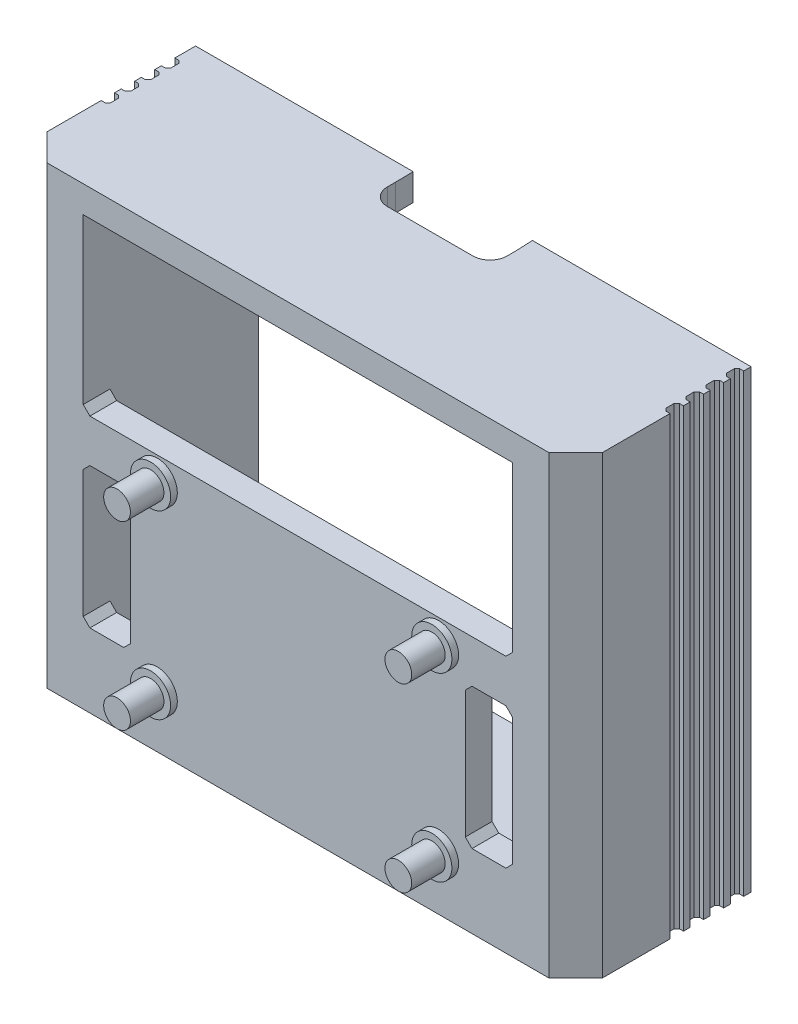
SolidWorks part; units mm, degrees
ref_plane "前视基准面" through (0, 0, 0) normal (0, 0, 1) x (1, 0, 0)
ref_plane "上视基准面" through (0, 0, 0) normal (0, 1, 0) x (1, 0, 0)
ref_plane "右视基准面" through (0, 0, 0) normal (1, 0, 0) x (0, 0, -1)
sketch "草图1" plane through (0, 0, 0) normal (0, 0, 1) x (1, 0, 0)
  line L4 (-16.0288, 20.4363) -> (-20.7373, 20.4363)
  line L5 (-20.7373, 20.4363) -> (-20.7373, -9.5383)
  line L6 (-20.7373, -9.5383) -> (-16.0288, -9.5383)
  line L7 (-16.0288, -9.5383) -> (-16.0288, 20.4363)
  line L8 (-16.0288, 20.4363) -> (-20.7373, 20.4363)
  line L9 (-20.7373, 20.4363) -> (-20.7373, -9.5383)
  line L10 (-20.7373, -9.5383) -> (-16.0288, -9.5383)
  line L11 (-16.0288, -9.5383) -> (-16.0288, 20.4363)
  line L12 (20.7373, -9.5383) -> (20.7373, 20.4363)
  line L13 (20.7373, 20.4363) -> (16.0288, 20.4363)
  line L14 (16.0288, 20.4363) -> (16.0288, -9.5383)
  line L15 (16.0288, -9.5383) -> (20.7373, -9.5383)
  line L16 (20.7373, -9.5383) -> (20.7373, 20.4363)
  line L17 (20.7373, 20.4363) -> (16.0288, 20.4363)
  line L18 (16.0288, 20.4363) -> (16.0288, -9.5383)
  line L19 (16.0288, -9.5383) -> (20.7373, -9.5383)
  dimension "D1" = 0
  dimension "D2" = 0
extrude "凸台-拉伸1" add sketch "草图1" along normal up to vertex (4.1 mm away)
sketch "草图2" plane through (0, 0, 4.1) normal (0, 0, 1) x (1, 0, 0)
  line L4 (-16.0288, -9.5383) -> (-16.0288, 20.4363)
  line L5 (-16.0288, 20.4363) -> (-20.7373, 20.4363)
  line L6 (-20.7373, 20.4363) -> (-20.7373, -9.5383)
  line L7 (-20.7373, -9.5383) -> (-16.0288, -9.5383)
  line L8 (-16.0288, -9.5383) -> (-16.0288, 20.4363)
  line L9 (-16.0288, 20.4363) -> (-20.7373, 20.4363)
  line L10 (-20.7373, 20.4363) -> (-20.7373, -9.5383)
  line L11 (-20.7373, -9.5383) -> (-16.0288, -9.5383)
  line L12 (16.0288, -9.5383) -> (20.7373, -9.5383)
  line L13 (20.7373, -9.5383) -> (20.7373, 20.4363)
  line L14 (20.7373, 20.4363) -> (16.0288, 20.4363)
  line L15 (16.0288, 20.4363) -> (16.0288, -9.5383)
  line L16 (16.0288, -9.5383) -> (20.7373, -9.5383)
  line L17 (20.7373, -9.5383) -> (20.7373, 20.4363)
  line L18 (20.7373, 20.4363) -> (16.0288, 20.4363)
  line L19 (16.0288, 20.4363) -> (16.0288, -9.5383)
  dimension "D1" = 0
  dimension "D2" = 0
extrude "凸台-拉伸2" add sketch "草图2" along normal blind 9
sketch "草图3" plane through (16.0288, 0, 0) normal (-1, 0, 0) x (0, 0, 1)
  line L0 (13.1, -9.5383) -> (7.1, -9.5383)
  line L1 (7.1, -9.5383) -> (7.1, 20.4363)
  line L4 (0, 20.4363) -> (0, -9.5383)
  line L5 (0, -9.5383) -> (13.1, -9.5383)
  line L6 (13.1, -9.5383) -> (13.1, 20.4363)
  line L7 (13.1, 20.4363) -> (0, 20.4363)
  line L9 (7.1, -9.5383) -> (13.1, -9.5383)
  line L10 (13.1, -9.5383) -> (13.1, 20.4363)
  line L11 (13.1, 20.4363) -> (7.1, 20.4363)
  line M6 (0, -9.5383) -> (13.1, -9.5383)
  line M7 (13.1, -9.5383) -> (13.1, 20.4363)
  line M8 (13.1, 20.4363) -> (0, 20.4363)
  dimension "D1" = 0
extrude "凸台-拉伸3" add sketch "草图3" along normal up to surface (32.0576 mm away) contours L1 M6 M7 M8 up to face at (-16.0288, 5.449, 6.55)
sketch "草图5" plane through (0, -9.5383, 0) normal (0, -1, 0) x (-1, 0, 0)
  line L0 (0, -13.1) -> (0, -15.0617)
  line L1 (20.7373, -13.1) -> (-20.7373, -13.1) construction
sketch "草图6" plane through (0, 0, 13.1) normal (0, 0, 1) x (1, 0, 0)
  circle A0 centre (-10.5, 5.9617) radius 1 construction
  circle A1 centre (-10.5, 5.9617) radius 1
  circle A3 centre (10.5, -7.5383) radius 1 construction
  circle A4 centre (-10.5, -7.5383) radius 1 construction
  circle A6 centre (10.5, -7.5383) radius 1
  circle A7 centre (-10.5, -7.5383) radius 1
  circle A8 centre (10.5, 5.9617) radius 1 construction
  circle A9 centre (10.5, 5.9617) radius 1
extrude "凸台-拉伸4" add sketch "草图6" along normal blind 3
sketch "草图7" plane through (0, 0, 13.1) normal (0, 0, 1) x (1, 0, 0)
  circle A0 centre (-10.5, 5.9617) radius 1.5
  circle A1 centre (-10.5, -7.5383) radius 1.5
  circle A2 centre (10.5, -7.5383) radius 1.5
  circle A3 centre (10.5, 5.9617) radius 1.5
extrude "凸台-拉伸5" add sketch "草图7" along normal blind 0.5
sketch "草图9" plane through (0, 0, 13.1) normal (0, 0, 1) x (1, 0, 0)
  line L0 (9.5, 14.4617) -> (-9.5, 14.4617) construction
  line L1 (16.0288, 14.4617) -> (-16.0288, 14.4617)
  line L4 (-16.0288, -9.5383) -> (16.0288, -9.5383)
  line L5 (-16.0288, 20.4363) -> (-16.0288, -9.5383)
  line L6 (16.0288, 20.4363) -> (-16.0288, 20.4363)
  line L7 (16.0288, -9.5383) -> (16.0288, 20.4363)
  line L9 (-16.0288, 20.4363) -> (-16.0288, 14.4617)
  line L10 (16.0288, 20.4363) -> (-16.0288, 20.4363)
  line L11 (16.0288, 14.4617) -> (16.0288, 20.4363)
  dimension "D1" = 0
extrude "切除-拉伸1" cut sketch "草图9" against normal up to next
sketch "草图11" plane through (0, -9.5383, 0) normal (0, -1, 0) x (1, 0, 0)
  line L8 (-20.7373, 0) -> (-16.0288, 0)
  line L9 (-16.0288, 0) -> (-16.0288, 7.1)
  line L10 (-16.0288, 7.1) -> (16.0288, 7.1)
  line L11 (16.0288, 7.1) -> (16.0288, 0)
  line L12 (16.0288, 0) -> (20.7373, 0)
  line L13 (20.7373, 0) -> (20.7373, 13.1)
  line L14 (20.7373, 13.1) -> (-20.7373, 13.1)
  line L15 (-20.7373, 13.1) -> (-20.7373, 0)
  line L16 (-20.7373, 0) -> (-16.0288, 0)
  line L17 (-16.0288, 0) -> (-16.0288, 7.1)
  line L18 (-16.0288, 7.1) -> (16.0288, 7.1)
  line L19 (16.0288, 7.1) -> (16.0288, 0)
  line L20 (16.0288, 0) -> (20.7373, 0)
  line L21 (20.7373, 0) -> (20.7373, 13.1)
  line L22 (20.7373, 13.1) -> (-20.7373, 13.1)
  line L23 (-20.7373, 13.1) -> (-20.7373, 0)
  dimension "D1" = 0
extrude "凸台-拉伸6" add sketch "草图11" along normal up to surface (2 mm away)
sketch "草图12" plane through (0, 20.4363, 0) normal (0, 1, 0) x (1, 0, 0)
  line L4 (16.0288, 0) -> (16.0288, -13.1)
  line L5 (16.0288, -13.1) -> (20.7373, -13.1)
  line L6 (20.7373, -13.1) -> (20.7373, 0)
  line L7 (20.7373, 0) -> (16.0288, 0)
  line L8 (16.0288, 0) -> (16.0288, -13.1)
  line L9 (16.0288, -13.1) -> (20.7373, -13.1)
  line L10 (20.7373, -13.1) -> (20.7373, 0)
  line L11 (20.7373, 0) -> (16.0288, 0)
  line L12 (-20.7373, -13.1) -> (-16.0288, -13.1)
  line L13 (-16.0288, -13.1) -> (-16.0288, 0)
  line L14 (-16.0288, 0) -> (-20.7373, 0)
  line L15 (-20.7373, 0) -> (-20.7373, -13.1)
  line L16 (-20.7373, -13.1) -> (-16.0288, -13.1)
  line L17 (-16.0288, -13.1) -> (-16.0288, 0)
  line L18 (-16.0288, 0) -> (-20.7373, 0)
  line L19 (-20.7373, 0) -> (-20.7373, -13.1)
  dimension "D1" = 0
  dimension "D2" = 0
extrude "凸台-拉伸7" add sketch "草图12" along normal up to surface (2 mm away)
sketch "草图13" plane through (0, 14.4617, 0) normal (0, 1, 0) x (1, 0, 0)
  line L4 (-16.0288, -7.1) -> (-16.0288, -13.1)
  line L5 (-16.0288, -13.1) -> (16.0288, -13.1)
  line L6 (16.0288, -13.1) -> (16.0288, -7.1)
  line L7 (16.0288, -7.1) -> (-16.0288, -7.1)
  line L8 (-16.0288, -7.1) -> (-16.0288, -13.1)
  line L9 (-16.0288, -13.1) -> (16.0288, -13.1)
  line L10 (16.0288, -13.1) -> (16.0288, -7.1)
  line L11 (16.0288, -7.1) -> (-16.0288, -7.1)
  dimension "D1" = 0
extrude "切除-拉伸3" cut sketch "草图13" against normal blind 6.8
sketch "草图14" plane through (0, 0, 13.1) normal (0, 0, 1) x (1, 0, 0)
  line L1 (-12.5, 4.4617) -> (-16.0288, 4.4617)
  line L2 (-12.5, -6.0383) -> (-16.0288, -6.0383)
  line L3 (-16.0288, 4.4617) -> (-16.0288, -6.0383)
  line L4 (-12.5, 4.4617) -> (-12.5, -6.0383)
  line L8 (12.5, 4.4617) -> (12.5, -6.0383)
  line L9 (12.5, -6.0383) -> (16.0288, -6.0383)
  line L10 (16.0288, 4.4617) -> (16.0288, -6.0383)
  line L11 (12.5, 4.4617) -> (16.0288, 4.4617)
extrude "切除-拉伸4" cut sketch "草图14" against normal up to next
chamfer "倒角1" distance 2 angle 45 2 edges at (20.7373, 5.449, 13.1) (-20.7373, 5.449, 13.1)
chamfer "倒角2" distance 0.5 angle 45 10 edges at (16.0288, -6.0383, 10.1) (12.5, -6.0383, 10.1) (16.0288, 4.4617, 10.1) (12.5, 4.4617, 10.1) (16.0288, 7.6617, 10.1) (-16.0288, -6.0383, 10.1) (-12.5, -6.0383, 10.1) (-12.5, 4.4617, 10.1) (-16.0288, 4.4617, 10.1) (-16.0288, 7.6617, 10.1)
sketch "草图15" plane through (0, -11.5383, 0) normal (0, -1, 0) x (1, 0, 0)
  line L0 (-20.7373, 5.55) -> (-20.2373, 5.55)
  line L1 (-20.7373, 0) -> (-20.7373, 11.1) construction
  line L2 (-20.2373, 5.55) -> (-20.2373, 4.55)
  line L3 (-20.2373, 4.55) -> (-20.7373, 4.55)
  line L4 (-20.7373, 4.55) -> (-20.7373, 5.55)
  line L5 (-20.7373, 4.05) -> (-20.2373, 4.05)
  line L6 (-20.2373, 4.05) -> (-20.2373, 3.05)
  line L7 (-20.2373, 3.05) -> (-20.7373, 3.05)
  line L8 (-20.7373, 3.05) -> (-20.7373, 4.05)
  line L9 (-20.7373, 2.55) -> (-20.2373, 2.55)
  line L10 (-20.2373, 2.55) -> (-20.2373, 1.55)
  line L11 (-20.2373, 1.55) -> (-20.7373, 1.55)
  line L12 (-20.7373, 1.55) -> (-20.7373, 2.55)
  line L13 (-20.7373, 7.05) -> (-20.2373, 7.05)
  line L14 (-20.2373, 7.05) -> (-20.2373, 6.05)
  line L15 (-20.2373, 6.05) -> (-20.7373, 6.05)
  line L16 (-20.7373, 6.05) -> (-20.7373, 7.05)
  line L19 (20.7373, 6.05) -> (20.7373, 5.05)
  line L20 (20.2373, 6.05) -> (20.7373, 6.05)
  line L21 (20.2373, 5.05) -> (20.2373, 6.05)
  line L22 (20.7373, 5.05) -> (20.2373, 5.05)
  line L23 (20.7373, 1.55) -> (20.7373, 0.55)
  line L24 (20.2373, 1.55) -> (20.7373, 1.55)
  line L25 (20.2373, 0.55) -> (20.2373, 1.55)
  line L26 (20.7373, 0.55) -> (20.2373, 0.55)
  line L27 (20.7373, 3.05) -> (20.7373, 2.05)
  line L28 (20.2373, 3.05) -> (20.7373, 3.05)
  line L29 (20.2373, 2.05) -> (20.2373, 3.05)
  line L30 (20.7373, 2.05) -> (20.2373, 2.05)
  line L31 (20.7373, 4.55) -> (20.7373, 3.55)
  line L32 (20.2373, 4.55) -> (20.7373, 4.55)
  line L33 (20.2373, 3.55) -> (20.2373, 4.55)
  line L34 (20.7373, 3.55) -> (20.2373, 3.55)
  dimension "D1" = 3
  dimension "D2" = 2
extrude "切除-拉伸5" cut sketch "草图15" against normal up to next
chamfer "倒角3" distance 0.2 angle 45 8 edges at (-20.2373, 5.449, 1.55) (-20.2373, 5.449, 3.05) (-20.2373, 5.449, 4.55) (-20.2373, 5.449, 6.05) (-20.2373, 5.449, 2.55) (-20.2373, 5.449, 4.05) (-20.2373, 5.449, 5.55) (-20.2373, 5.449, 7.05)
chamfer "倒角4" distance 0.2 angle 45 8 edges at (20.2373, 5.449, 5.05) (20.2373, 5.449, 3.55) (20.2373, 5.449, 2.05) (20.2373, 5.449, 0.55) (20.2373, 5.449, 1.55) (20.2373, 5.449, 3.05) (20.2373, 5.449, 4.55) (20.2373, 5.449, 6.05)
sketch "草图16" plane through (0, 0, 0) normal (0, 0, -1) x (-1, 0, 0)
  line L0 (-16.0288, 22.4363) -> (16.0288, 22.4363)
  line L1 (16.0288, 22.4363) -> (16.0288, 20.4363)
  line L2 (16.0288, -11.5383) -> (16.0288, 22.4363) construction
  line L3 (-20.7373, 20.4363) -> (20.7373, 20.4363) construction
  line L4 (16.0288, 20.4363) -> (-16.0288, 20.4363)
  line L5 (-16.0288, 22.4363) -> (-16.0288, -11.5383) construction
  line L6 (-16.0288, 20.4363) -> (-16.0288, 22.4363)
extrude "凸台-拉伸8" add sketch "草图16" against normal up to surface (13.1 mm away) up to face at (-14.2644, -0.7883, 13.1)
sketch "草图17" plane through (0, 20.4363, 0) normal (0, -1, 0) x (1, 0, 0)
  line L0 (4.4706, 1.3435) -> (4.4706, 1.9435) construction
  line L2 (-4.4694, 1.3435) -> (-4.4694, 1.9435) construction
  line L3 (3.1906, 3.2235) -> (-3.1894, 3.2235) construction
  line L4 (4.4706, 1.3435) -> (4.4706, 1.9435)
  line L6 (-4.4694, 1.3435) -> (-4.4694, 1.9435)
  line L7 (3.1906, 3.2235) -> (-3.1894, 3.2235)
  line L8 (-4.4694, 1.3435) -> (-4.4892, 0)
  line L9 (-4.4892, 0) -> (4.4108, 0)
  line L10 (4.4706, 1.3435) -> (4.4108, 0)
  arc A0 (-3.1894, 3.2235) -> (-4.4694, 1.9435) centre (-3.1894, 1.9435) ccw construction
  arc A1 (-3.1894, 3.2235) -> (-4.4694, 1.9435) centre (-3.1894, 1.9435) ccw
  ellipse E0 centre (3.1906, 1.3435) end of major axis (3.4996, 2.5856) minor radius 1.28 (3.1906, 0.0635) -> (4.4706, 1.3435) ccw construction
  ellipse E1 centre (3.1906, 1.9435) end of major axis (2.8816, 0.7013) minor radius 1.28 (4.4706, 1.9435) -> (3.1906, 3.2235) ccw construction
  ellipse E3 centre (3.1906, 1.3435) end of major axis (3.4996, 2.5856) minor radius 1.28 (4.4656, 1.2298) -> (4.4706, 1.3435) ccw
  ellipse E4 centre (3.1906, 1.9435) end of major axis (2.8816, 0.7013) minor radius 1.28 (4.4706, 1.9435) -> (3.1906, 3.2235) ccw
  line M12 (-16.0288, 0) -> (16.0288, 0)
extrude "切除-拉伸7" cut sketch "草图17" against normal up to next contours L4 E4 L7 A1 L6 L8 L10 M12
sketch "草图18" plane through (0, 0, 7.1) normal (0, 0, -1) x (-1, 0, 0)
  line L0 (-16.0288, -11.5383) -> (16.0288, -11.5383)
  line L1 (16.0288, -11.5383) -> (16.0288, -9.5383)
  line L2 (16.0288, -11.5383) -> (16.0288, 20.4363) construction
  line L3 (20.7373, -9.5383) -> (-20.7373, -9.5383) construction
  line L4 (16.0288, -9.5383) -> (-16.0288, -9.5383)
  line L5 (-16.0288, 20.4363) -> (-16.0288, -11.5383) construction
  line L6 (-16.0288, -9.5383) -> (-16.0288, -11.5383)
extrude "凸台-拉伸9" add sketch "草图18" along normal up to surface (7.1 mm away) up to face at (13.7257, 10.4448, 0)
sketch "草图19" plane through (0, 0, 7.1) normal (0, 0, -1) x (-1, 0, 0)
  line L22 (-16.0288, -5.5383) -> (-16.0288, -9.5383)
  line L23 (-16.0288, -9.5383) -> (16.0288, -9.5383)
  line L24 (16.0288, -9.5383) -> (16.0288, -5.5383)
  line L25 (16.0288, -5.5383) -> (15.5288, -6.0383)
  line L26 (15.5288, -6.0383) -> (13, -6.0383)
  line L27 (13, -6.0383) -> (12.5, -5.5383)
  line L28 (12.5, -5.5383) -> (12.5, 3.9617)
  line L29 (12.5, 3.9617) -> (13, 4.4617)
  line L30 (13, 4.4617) -> (15.5288, 4.4617)
  line L31 (15.5288, 4.4617) -> (16.0288, 3.9617)
  line L32 (16.0288, 3.9617) -> (16.0288, 8.1617)
  line L33 (16.0288, 8.1617) -> (15.5288, 7.6617)
  line L34 (15.5288, 7.6617) -> (-15.5288, 7.6617)
  line L35 (-15.5288, 7.6617) -> (-16.0288, 8.1617)
  line L36 (-16.0288, 8.1617) -> (-16.0288, 3.9617)
  line L37 (-16.0288, 3.9617) -> (-15.5288, 4.4617)
  line L38 (-15.5288, 4.4617) -> (-13, 4.4617)
  line L39 (-13, 4.4617) -> (-12.5, 3.9617)
  line L40 (-12.5, 3.9617) -> (-12.5, -5.5383)
  line L41 (-12.5, -5.5383) -> (-13, -6.0383)
  line L42 (-13, -6.0383) -> (-15.5288, -6.0383)
  line L43 (-15.5288, -6.0383) -> (-16.0288, -5.5383)
  line L44 (-16.0288, -5.5383) -> (-16.0288, -9.5383)
  line L45 (-16.0288, -9.5383) -> (16.0288, -9.5383)
  line L46 (16.0288, -9.5383) -> (16.0288, -5.5383)
  line L47 (16.0288, -5.5383) -> (15.5288, -6.0383)
  line L48 (15.5288, -6.0383) -> (13, -6.0383)
  line L49 (13, -6.0383) -> (12.5, -5.5383)
  line L50 (12.5, -5.5383) -> (12.5, 3.9617)
  line L51 (12.5, 3.9617) -> (13, 4.4617)
  line L52 (13, 4.4617) -> (15.5288, 4.4617)
  line L53 (15.5288, 4.4617) -> (16.0288, 3.9617)
  line L54 (16.0288, 3.9617) -> (16.0288, 8.1617)
  line L55 (16.0288, 8.1617) -> (15.5288, 7.6617)
  line L56 (15.5288, 7.6617) -> (-15.5288, 7.6617)
  line L57 (-15.5288, 7.6617) -> (-16.0288, 8.1617)
  line L58 (-16.0288, 8.1617) -> (-16.0288, 3.9617)
  line L59 (-16.0288, 3.9617) -> (-15.5288, 4.4617)
  line L60 (-15.5288, 4.4617) -> (-13, 4.4617)
  line L61 (-13, 4.4617) -> (-12.5, 3.9617)
  line L62 (-12.5, 3.9617) -> (-12.5, -5.5383)
  line L63 (-12.5, -5.5383) -> (-13, -6.0383)
  line L64 (-13, -6.0383) -> (-15.5288, -6.0383)
  line L65 (-15.5288, -6.0383) -> (-16.0288, -5.5383)
  dimension "D1" = 0
extrude "切除-拉伸8" cut sketch "草图19" against normal blind 4
